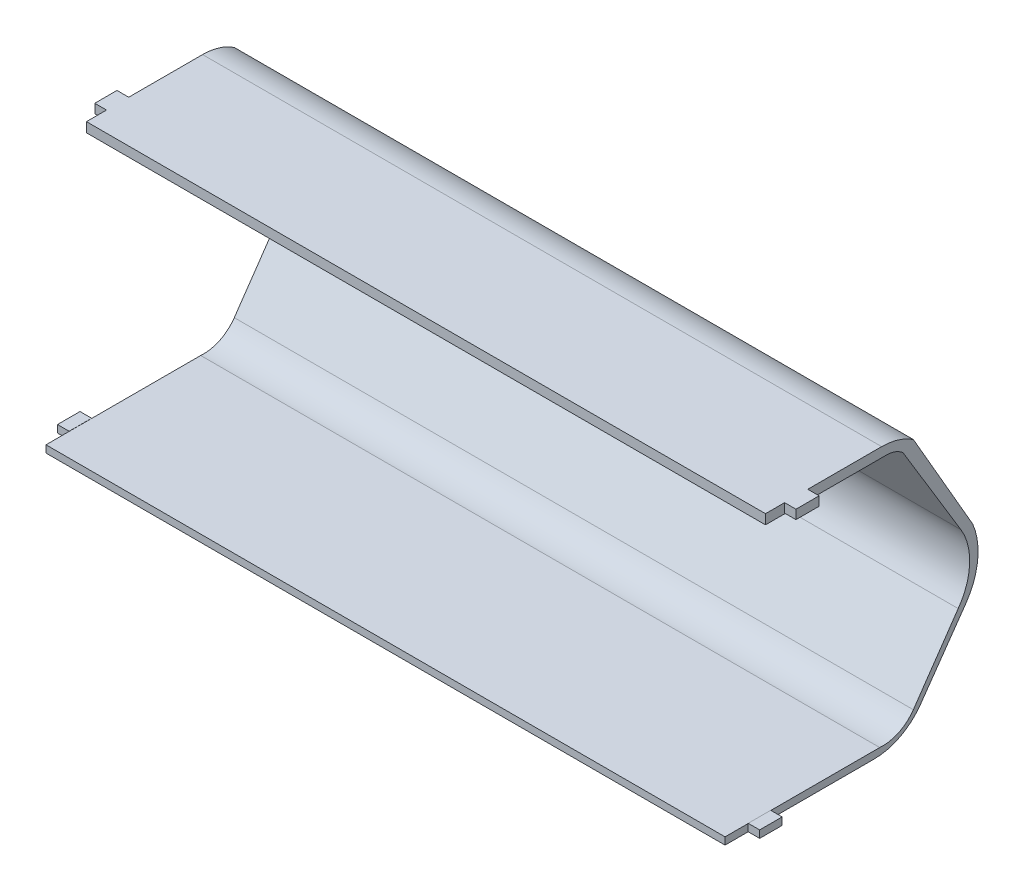
SolidWorks part; units mm, degrees
ref_plane "Front Plane" through (0, 0, 0) normal (0, 0, 1) x (1, 0, 0)
ref_plane "Top Plane" through (0, 0, 0) normal (0, 1, 0) x (1, 0, 0)
ref_plane "Right Plane" through (0, 0, 0) normal (1, 0, 0) x (0, 0, -1)
sketch "Sketch1" plane through (0, 0, 0) normal (1, 0, 0) x (0, 0, -1)
  line L0 (-32.6036, 33.0477) -> (-6.5802, 33.0477)
  line L1 (0.5234, 30.8752) -> (13.8146, 7.8513)
  line L2 (-41.6652, -25.1276) -> (-7.01, -25.1276)
  line L3 (12.2656, -6.8586) -> (2.1141, -21.3337)
  line L4 (-8.2837, -26.7416) -> (-41.6652, -26.7416)
  line L5 (0.5234, -21.5552) -> (10.5722, -6.9542)
  line L6 (-32.6036, 30.8752) -> (-5.4693, 30.8752)
  line L7 (-1.7961, 29.486) -> (11.1852, 8.0467)
  line L8 (-32.6036, 33.0477) -> (-32.6036, 30.8752)
  line L9 (-41.6652, -25.1276) -> (-41.6652, -26.7416)
  arc A0 (12.2656, -6.8586) -> (13.8146, 7.8513) centre (-0.2119, 1.8919) ccw
  arc A1 (-8.2837, -26.7416) -> (2.1141, -21.3337) centre (-8.2837, -14.0416) ccw
  arc A2 (-6.5802, 33.0477) -> (0.5234, 30.8752) centre (-6.5802, 20.3477) cw
  arc A3 (0.5234, -21.5552) -> (-7.01, -25.1276) centre (-6.3255, -16.8416) cw
  arc A4 (11.1852, 8.0467) -> (10.5722, -6.9542) centre (-0.4385, 1.0087) cw
  arc A5 (-5.4693, 30.8752) -> (-1.7961, 29.486) centre (-5.4693, 25.3246) cw
  dimension "D1" = 15.24
  dimension "D2" = 12.7
  dimension "D3" = 12.7
extrude "Boss-Extrude1" add sketch "Sketch1" along normal blind 152.146
sketch "Sketch2" plane through (0, 33.0477, 0) normal (0, 1, 0) x (1, 0, 0)
  line L0 (0, -23.129) -> (-2.6298, -23.129)
  line L1 (0, -6.5802) -> (0, -32.6036) construction
  line L2 (-2.6298, -23.129) -> (-2.6298, -28.1084)
  line L3 (-2.6298, -28.1084) -> (0, -28.1084)
  line L4 (0, -28.1084) -> (0, -23.129)
  line L6 (152.146, -23.129) -> (154.6855, -23.129)
  line L7 (152.146, -6.5802) -> (152.146, -32.6036) construction
  line L8 (154.6855, -23.129) -> (154.6855, -28.3219)
  line L9 (154.6855, -28.3219) -> (152.146, -28.3219)
  line L10 (152.146, -28.3219) -> (152.146, -23.129)
  dimension "D1" = 2.5395
  dimension "D2" = 2.5395
  dimension "D3" = 5.1929
extrude "Boss-Extrude3" add sketch "Sketch2" against normal blind 2.032
sketch "Sketch3" plane through (0, -26.7416, 0) normal (0, -1, 0) x (1, 0, 0)
  line L0 (0, 31.437) -> (-2.6086, 31.437)
  line L1 (0, 41.6652) -> (0, 8.2837) construction
  line L2 (-2.6086, 31.437) -> (-2.6086, 36.4824)
  line L3 (-2.6086, 36.4824) -> (0, 36.4824)
  line L4 (0, 36.4824) -> (0, 31.437)
  line L12 (152.146, 31.437) -> (154.7144, 31.437)
  line L13 (152.146, 41.6652) -> (152.146, 8.2837) construction
  line L14 (154.7144, 31.437) -> (154.7144, 36.4824)
  line L15 (154.7144, 36.4824) -> (152.146, 36.4824)
  line L16 (152.146, 36.4824) -> (152.146, 31.437)
extrude "Boss-Extrude4" add sketch "Sketch3" against normal blind 1.651
